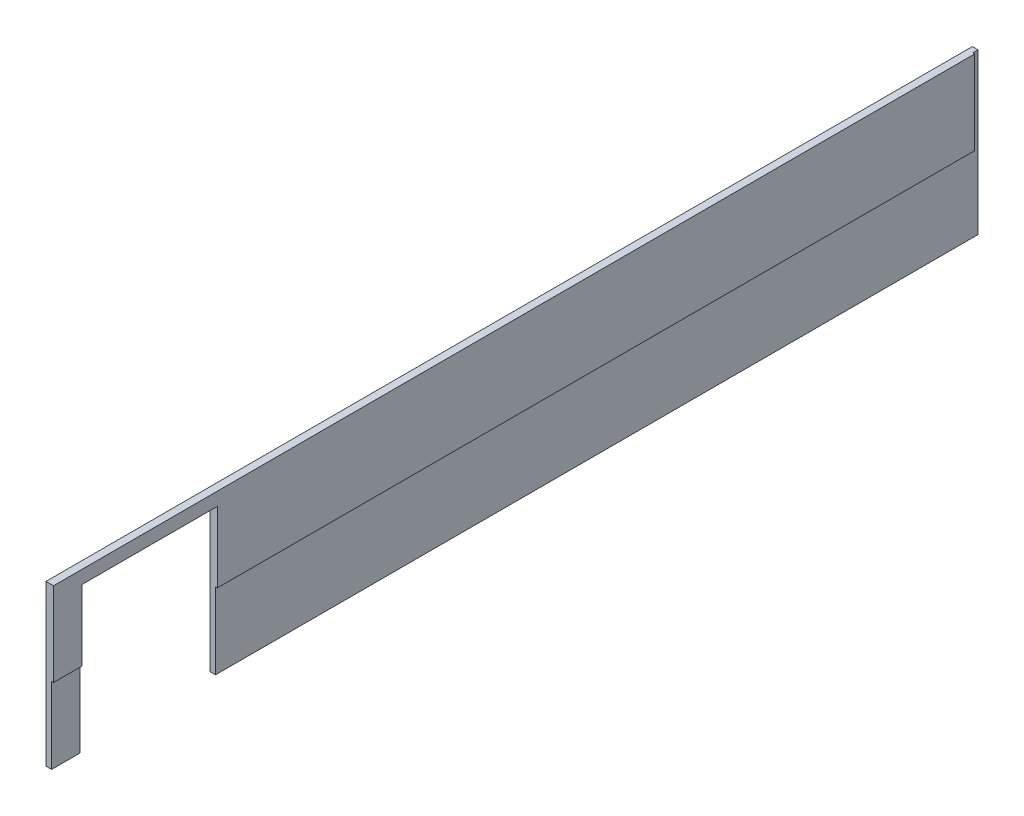
SolidWorks part; units mm, degrees
ref_plane "Front Plane" through (0, 0, 0) normal (0, 0, 1) x (1, 0, 0)
ref_plane "Top Plane" through (0, 0, 0) normal (0, 1, 0) x (1, 0, 0)
ref_plane "Right Plane" through (0, 0, 0) normal (1, 0, 0) x (0, 0, -1)
sketch "Sketch1" plane through (0, 0, 0) normal (1, 0, 0) x (0, 0, -1)
  line L1 (0, 0) -> (12496.8, 0)
  line L2 (0, 0) -> (0, 2159)
  line L3 (0, 2159) -> (12496.8, 2159)
  line L4 (12496.8, 0) -> (12496.8, 2159)
  dimension "D1" = 12496.8
  dimension "D2" = 2159
extrude "Boss-Extrude1" add sketch "Sketch1" along normal blind 76.2
sketch "Sketch3" plane through (76.2, 0, 0) normal (1, 0, 0) x (0, 0, -1)
  line L0 (12496.8, 2159) -> (0, 2159) construction
  line L1 (0, 1028.7) -> (12426.8751, 1028.7)
  line L2 (0, 1028.7) -> (0, 2159)
  line L3 (0, 2159) -> (12426.8751, 2159)
  line L4 (12426.8751, 1028.7) -> (12426.8751, 2159)
  line L5 (0, 0) -> (12496.8, 0) construction
  dimension "D1" = 1028.7
extrude "Boss-Extrude2" add sketch "Sketch3" along normal blind 25.4 contours L2 L1 L4 L3
sketch "Sketch2" plane through (0, 0, 0) normal (-1, 0, 0) x (0, 0, 1)
  line L0 (0, 0) -> (-12496.8, 0) construction
  line L1 (-381, 0) -> (-2209.8, 0)
  line L2 (-381, 0) -> (-381, 1981.2)
  line L3 (-381, 1981.2) -> (-2209.8, 1981.2)
  line L4 (-2209.8, 0) -> (-2209.8, 1981.2)
  line L5 (0, 2159) -> (0, 0) construction
  dimension "D1" = 1828.8
  dimension "D2" = 1981.2
  dimension "D3" = 381
extrude "Cut-Extrude1" cut sketch "Sketch2" against normal through all
sketch "Sketch4" plane through (101.6, 0, 0) normal (1, 0, 0) x (0, 0, -1)
  line L0 (2336.8, 1981.2) -> (2416.8, 1981.2) construction
  line L1 (2336.8, 1985) -> (2416.8, 1985)
  line L2 (2336.8, 1977.4) -> (2416.8, 1977.4)
  line L3 (2209.8, 1981.2) -> (12496.8, 1981.2) construction
  line L4 (12496.8, 0) -> (12496.8, 2159) construction
  arc A0 (2336.8, 1985) -> (2336.8, 1977.4) centre (2336.8, 1981.2) ccw
  arc A1 (2416.8, 1977.4) -> (2416.8, 1985) centre (2416.8, 1981.2) ccw
  point P2 (2376.8, 1981.2)
  point P8 (2376.8, 1978.66)
  point P16 (2508.626, 1981.2)
  dimension "D1" = 80
  dimension "D2" = 127
  dimension "D3" = 7.6
